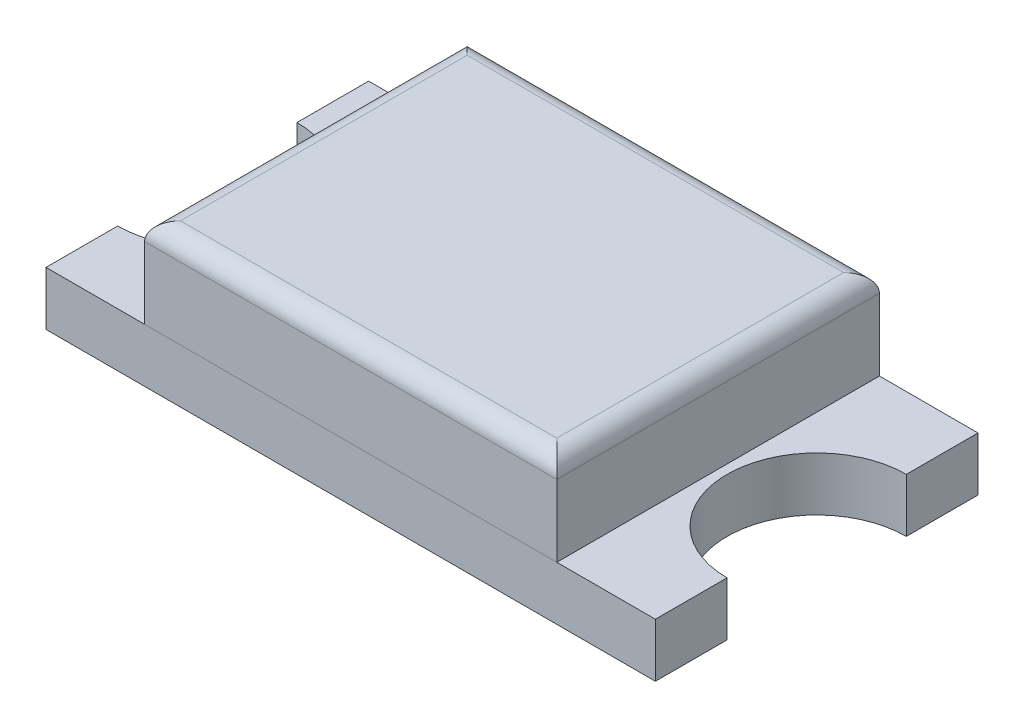
SolidWorks part; units mm, degrees
ref_plane "Front Plane" through (0, 0, 0) normal (0, 0, 1) x (1, 0, 0)
ref_plane "Top Plane" through (0, 0, 0) normal (0, 1, 0) x (1, 0, 0)
ref_plane "Right Plane" through (0, 0, 0) normal (1, 0, 0) x (0, 0, -1)
sketch "Sketch1" plane through (0, 0, 0) normal (0, 1, 0) x (1, 0, 0)
  line L0 (-0.85, -0.45) -> (0.85, -0.45)
  line L1 (-0.85, -0.45) -> (-0.85, -0.25)
  line L2 (0.85, -0.45) -> (0.85, -0.25)
  line L3 (-0.85, 0.45) -> (0.85, 0.45)
  line L4 (-0.85, -0.45) -> (0.85, 0.45) construction
  line L5 (0.85, -0.45) -> (-0.85, 0.45) construction
  line L6 (-0.85, 0.25) -> (-0.85, 0.45)
  line L7 (0.85, 0.25) -> (0.85, 0.45)
  arc A0 (-0.85, -0.25) -> (-0.85, 0.25) centre (-0.85, 0) ccw
  arc A1 (0.85, 0.25) -> (0.85, -0.25) centre (0.85, 0) ccw
  point P1 (0, 0)
  dimension "D1" = 1.7
  dimension "D2" = 0.9
extrude "Boss-Extrude1" add sketch "Sketch1" along normal blind 0.15
sketch "Sketch2" plane through (0, 0.15, 0) normal (0, 1, 0) x (1, 0, 0)
  line L0 (-0.575, -0.45) -> (0.575, -0.45)
  line L1 (-0.575, -0.45) -> (-0.575, 0.45)
  line L2 (0.575, -0.45) -> (0.575, 0.45)
  line L3 (-0.575, 0.45) -> (0.575, 0.45)
  line L4 (-0.575, -0.45) -> (0.575, 0.45) construction
  line L5 (0.575, -0.45) -> (-0.575, 0.45) construction
  line L6 (0.85, 0.45) -> (-0.85, 0.45) construction
  point P1 (0, 0)
  dimension "D1" = 1.15
extrude "Boss-Extrude2" add sketch "Sketch2" along normal blind 0.25 separate body
fillet "Fillet1" radius 0.05 4 edges at (0, 0.4, -0.45) (0.575, 0.4, 0) (-0.575, 0.4, 0) (0, 0.4, 0.45)
